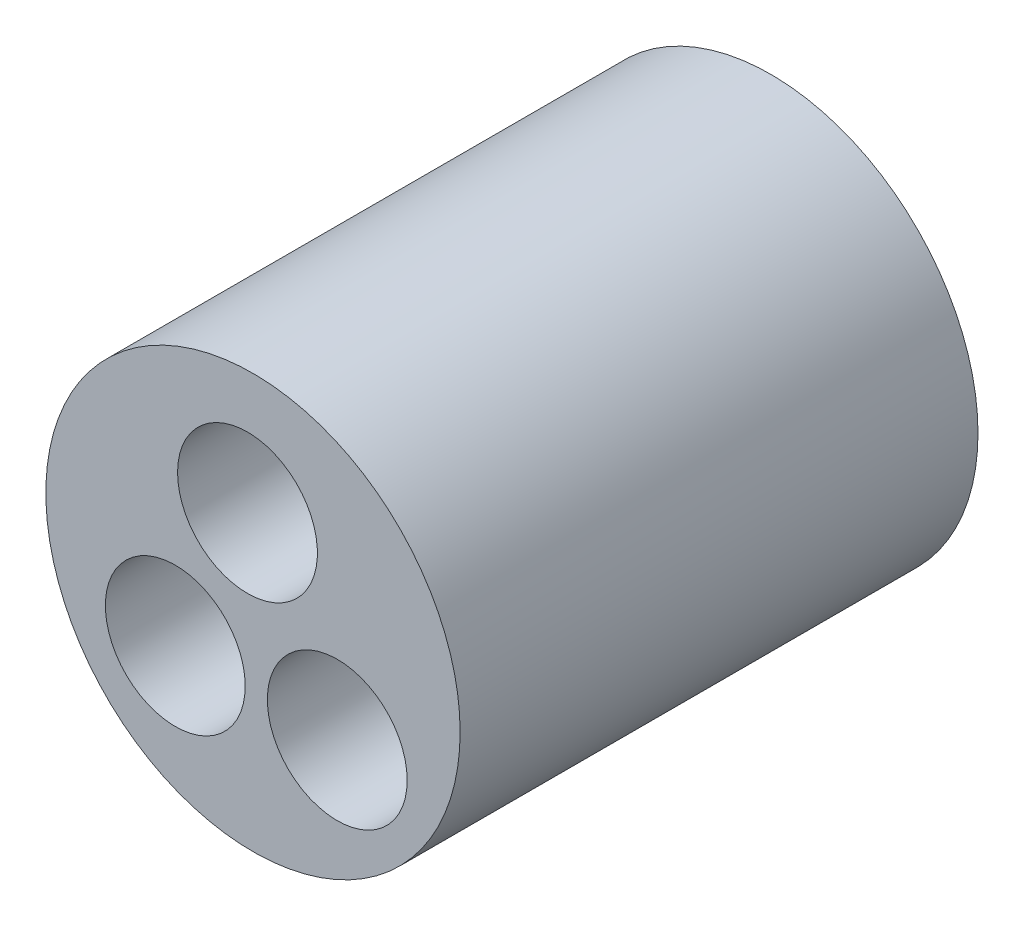
SolidWorks part; units mm, degrees
ref_plane "Front Plane" through (0, 0, 0) normal (0, 0, 1) x (1, 0, 0)
ref_plane "Top Plane" through (0, 0, 0) normal (0, 1, 0) x (1, 0, 0)
ref_plane "Right Plane" through (0, 0, 0) normal (1, 0, 0) x (0, 0, -1)
sketch "Sketch5" plane through (0, 0, 0) normal (0, 0, 1) x (1, 0, 0)
  circle A0 centre (7.58, 0) radius 4
  dimension "D1" = 8
extrude "Boss-Extrude2" add sketch "Sketch5" along normal blind 10 separate body
sketch "Sketch6" plane through (0, 0, 0) normal (0, 0, -1) x (-1, 0, 0)
  circle A0 centre (-7.58, 0) radius 2.75
  dimension "D1" = 5.5
extrude "Cut-Extrude4" cut sketch "Sketch6" against normal blind 5.2
sketch "Sketch7" plane through (0, 0, 5.2) normal (0, 0, -1) x (-1, 0, 0)
  line L0 (-7.58, 2.75) -> (-7.58, -2.75) construction
  line L1 (-10.33, 0) -> (-4.83, 0) construction
  circle A0 centre (-7.58, 0) radius 2.75 construction
  circle A1 centre (-7.58, 0) radius 2.75 construction
  circle A2 centre (-7.58, 0) radius 2.2
  dimension "D1" = 4.4
extrude "Cut-Extrude5" cut sketch "Sketch7" against normal blind 1
sketch "Sketch9" plane through (-0.8086, 0.6834, 6.2) normal (0, 0, -1) x (-1, 0, 0)
  circle A2 centre (-8.2822, 0.9322) radius 1.35
  point P0 (-8.2822, 0.9322)
  point P11 (-7.58, 0)
  dimension "D1" = 2.7
extrude "Cut-Extrude6" cut sketch "Sketch9" against normal through all
sketch "Sketch10" plane through (0, 0, 10) normal (0, 0, 1) x (1, 0, 0)
  circle A2 centre (6.0796, -1.3074) radius 1.35
  point P0 (6.0796, -1.3074)
  point P11 (6.7818, -2.2397)
  dimension "D1" = 2.7
extrude "Cut-Extrude7" cut sketch "Sketch10" against normal through all
sketch "Sketch11" plane through (0, 0.7493, 10) normal (0, 0, 1) x (1, 0, 0)
  circle A2 centre (9.2075, -2.0674) radius 1.35
  point P0 (9.2075, -2.0674)
  point P11 (9.9098, -2.9996)
  dimension "D1" = 2.7
extrude "Cut-Extrude8" cut sketch "Sketch11" against normal through all
